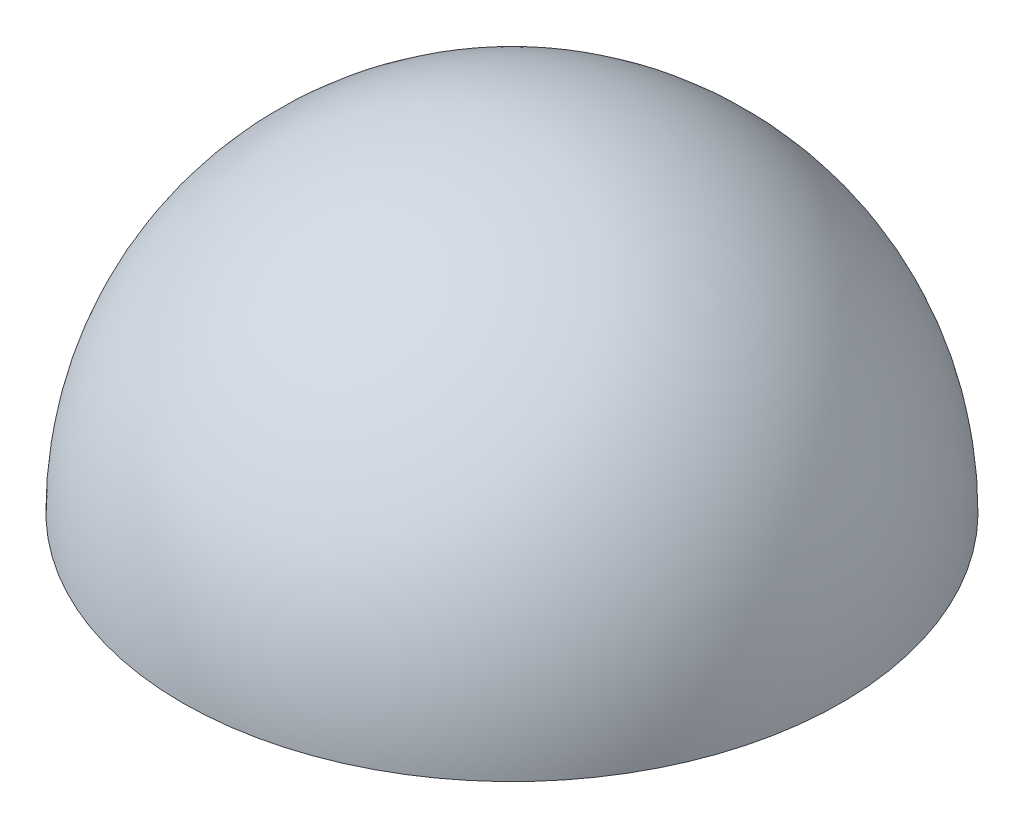
SolidWorks part; units mm, degrees
ref_plane "Front Plane" through (0, 0, 0) normal (0, 0, 1) x (1, 0, 0)
ref_plane "Top Plane" through (0, 0, 0) normal (0, 1, 0) x (1, 0, 0)
ref_plane "Right Plane" through (0, 0, 0) normal (1, 0, 0) x (0, 0, -1)
sketch "Sketch1" plane through (0, 0, 0) normal (0, 1, 0) x (1, 0, 0)
  line L0 (0, 0.8) -> (0, 0.7529)
  line L1 (0, -0.7529) -> (0, -0.8)
  arc A0 (0, -0.8) -> (0, 0.8) centre (0, 0) ccw
  arc A1 (0, -0.7529) -> (0, 0.7529) centre (0, 0) ccw
revolve "Revolve1" add sketch "Sketch1" angle 180 about L1
